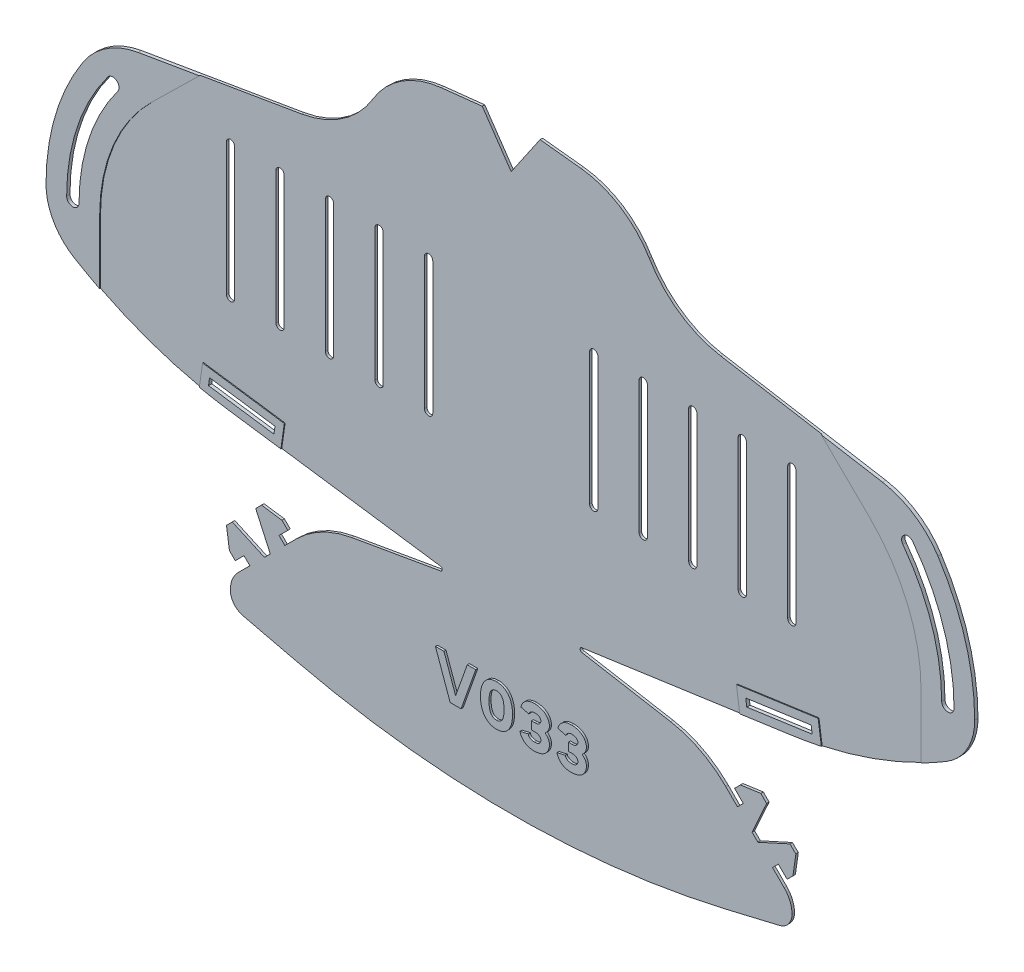
SolidWorks part; units mm, degrees
ref_plane "Front Plane" through (0, 0, 0) normal (0, 0, 1) x (1, 0, 0)
ref_plane "Top Plane" through (0, 0, 0) normal (0, 1, 0) x (1, 0, 0)
ref_plane "Right Plane" through (0, 0, 0) normal (1, 0, 0) x (0, 0, -1)
sketch "Sketch1" plane through (0, 0, 0) normal (0, 0, 1) x (1, 0, 0)
  line L0 (0, 0) -> (0, -145) construction
  line L1 (-14, -102) -> (14, -102) construction
  line L2 (-112.5, -69) -> (112.5, -69) construction
  line L3 (0, -10.2352) -> (-7, 0)
  line L4 (0, -10.2352) -> (7, 0)
  line L5 (7, 0) -> (16.9419, -1.0768)
  line L6 (-90.1804, -30.1909) -> (-50.7439, -23.5)
  line L7 (90.1804, -30.1909) -> (50.7439, -23.5)
  line L8 (-14, -102) -> (-68.2662, -94.2919)
  line L9 (-7, 0) -> (-16.9419, -1.0768)
  line L10 (14, -102) -> (68.2662, -94.2919)
  line L11 (-103.5977, -39) -> (-103.5977, -69) construction
  line L12 (-14, -102) -> (-38.6266, -106.305)
  line L13 (-52, -113.2546) -> (-54.8283, -116.0832)
  line L14 (52, -113.2546) -> (54.8283, -116.0832)
  line L15 (14, -102) -> (38.6266, -106.305)
  line L16 (-54.8283, -116.0832) -> (-56.2426, -114.669)
  line L17 (-56.2426, -114.669) -> (-54.1214, -112.5476)
  line L18 (-54.1214, -112.5476) -> (-55.5356, -111.1334)
  line L19 (-55.5356, -111.1334) -> (-60.4854, -110.4265)
  line L20 (-60.4854, -110.4265) -> (-68.9703, -118.9122)
  line L21 (-64.7275, -123.1546) -> (-63.3132, -124.5688)
  line L22 (-63.3132, -124.5688) -> (-66.1415, -127.3973)
  line L23 (-64.7275, -123.1546) -> (-66.8487, -125.2761)
  line L24 (-66.8487, -125.2761) -> (-68.263, -123.8619)
  line L25 (-68.9703, -118.9122) -> (-68.263, -123.8619)
  line L26 (68.9703, -118.9122) -> (68.263, -123.8619)
  line L27 (66.8487, -125.2761) -> (68.263, -123.8619)
  line L28 (64.7275, -123.1546) -> (66.8487, -125.2761)
  line L29 (63.3132, -124.5688) -> (66.1415, -127.3973)
  line L30 (64.7275, -123.1546) -> (63.3132, -124.5688)
  line L31 (60.4854, -110.4265) -> (68.9703, -118.9122)
  line L32 (55.5356, -111.1334) -> (60.4854, -110.4265)
  line L33 (54.1214, -112.5476) -> (55.5356, -111.1334)
  line L34 (56.2426, -114.669) -> (54.1214, -112.5476)
  line L35 (54.8283, -116.0832) -> (56.2426, -114.669)
  line L36 (-64.9691, -135.8852) -> (-52.4361, -138.8607)
  line L37 (64.9691, -135.8852) -> (52.4361, -138.8607)
  line L38 (-68.9703, -118.9122) -> (-64.7275, -123.1546) construction
  line L39 (-60.4854, -110.4265) -> (-56.2426, -114.669) construction
  arc A0 (-16.9419, -1.0768) -> (-33.4614, -11.6696) centre (-14.5729, -22.9489) ccw
  arc A1 (-33.4614, -11.6696) -> (-50.7439, -23.5) centre (-54.9257, 1.1478) cw
  arc A2 (-103.5977, -39) -> (-90.1804, -30.1909) centre (-86.8349, -49.9091) cw
  arc A3 (-112.5, -69) -> (-103.5977, -39) centre (-57.5, -69) cw
  arc A4 (112.5, -69) -> (103.5977, -39) centre (57.5, -69) ccw
  arc A5 (103.5977, -39) -> (90.1804, -30.1909) centre (86.8349, -49.9091) ccw
  arc A6 (16.9419, -1.0768) -> (33.4614, -11.6696) centre (14.5729, -22.9489) cw
  arc A7 (33.4614, -11.6696) -> (50.7439, -23.5) centre (54.9257, 1.1478) ccw
  arc A8 (-112.5, -69) -> (-105.7111, -81) centre (-98.5, -69) ccw
  arc A9 (-105.7111, -81) -> (-68.2662, -94.2919) centre (-54.2032, 4.7143) ccw
  arc A10 (112.5, -69) -> (105.7111, -81) centre (98.5, -69) cw
  arc A11 (105.7111, -81) -> (68.2662, -94.2919) centre (54.2032, 4.7143) cw
  arc A12 (-38.6266, -106.305) -> (-52, -113.2546) centre (-34.3216, -130.9315) ccw
  arc A13 (38.6266, -106.305) -> (52, -113.2546) centre (34.3216, -130.9315) cw
  arc A14 (-66.1415, -127.3973) -> (-68.0451, -131.9933) centre (-61.5451, -131.9933) ccw
  arc A15 (-68.0451, -131.9933) -> (-64.9691, -135.8852) centre (-64.0451, -131.9933) ccw
  arc A16 (68.0451, -131.9933) -> (64.9691, -135.8852) centre (64.0451, -131.9933) cw
  arc A17 (66.1415, -127.3973) -> (68.0451, -131.9933) centre (61.5451, -131.9933) cw
  arc A19 (-52.4361, -138.8607) -> (0, -145) centre (0, 82) ccw
  arc A20 (52.4361, -138.8607) -> (0, -145) centre (0, 82) cw
  point P8 (0, -102)
  point P11 (0, -69)
  dimension "D5" = 55
  dimension "D11" = 20
  dimension "D13" = 25
  dimension "D16" = 14
  dimension "D15" = 22
  dimension "D18" = 100
  dimension "D22" = 25
  dimension "D31" = 6.5
  dimension "D32" = 4
  dimension "D34" = 227
  dimension "D1" = 145
  dimension "D2" = 28
  dimension "D3" = 43
  dimension "D4" = 76
  dimension "D6" = 225
  dimension "D7" = 14
  dimension "D8" = 12.4
  dimension "D9" = 10
  dimension "D10" = 30
  dimension "D12" = 40
  dimension "D14" = 45.5
  dimension "D17" = 12
  dimension "D19" = 18
  dimension "D20" = 25
  dimension "D21" = 4
  dimension "D23" = 38
  dimension "D24" = 2
  dimension "D25" = 3
  dimension "D26" = 2
  dimension "D27" = 18
  dimension "D29" = 8
  dimension "D30" = 4
extrude "Main Shape" add sketch "Sketch1" along normal blind 0.6
sketch "Sketch2" plane through (0, 0, 0.6) normal (0, 0, 1) x (1, 0, 0)
  line L0 (0, -55) -> (0, 55) construction
  arc A0 (-96.3, -39.9) -> (-106, -69) centre (-57.5, -69) ccw construction
  arc A1 (-97.5, -39) -> (-107.5, -69) centre (-57.5, -69) ccw
  arc A2 (-95.1, -40.8) -> (-104.5, -69) centre (-57.5, -69) ccw
  arc A3 (-95.1, -40.8) -> (-97.5, -39) centre (-96.3, -39.9) ccw
  arc A4 (-107.5, -69) -> (-104.5, -69) centre (-106, -69) ccw
  arc A6 (-103.5977, -39) -> (-112.5, -69) centre (-57.5, -69) ccw construction
  arc A7 (96.3, -39.9) -> (106, -69) centre (57.5, -69) cw construction
  arc A8 (97.5, -39) -> (107.5, -69) centre (57.5, -69) cw
  arc A9 (95.1, -40.8) -> (104.5, -69) centre (57.5, -69) cw
  arc A10 (95.1, -40.8) -> (97.5, -39) centre (96.3, -39.9) cw
  arc A11 (107.5, -69) -> (104.5, -69) centre (106, -69) cw
  point P3 (-103.5111, -53.663)
  point P19 (103.5111, -53.663)
  dimension "D1" = 5
  dimension "D2" = 1.5
extrude "Elastic Attachment Points" cut sketch "Sketch2" against normal through all
sketch "Sketch7" plane through (0, 0, 0.6) normal (0, 0, 1) x (1, 0, 0)
  line L0 (-99.5, -69) -> (-99.5, -84.4384)
  line L1 (-86.8939, -39) -> (-75.3319, -27.6717)
  line L2 (-50.7439, -23.5) -> (-90.1804, -30.1909) construction
  line L3 (-75.3319, -27.6717) -> (-90.1804, -30.1909)
  line L4 (0, -55) -> (0, 55) construction
  line L5 (75.3319, -27.6717) -> (90.1804, -30.1909)
  line L6 (86.8939, -39) -> (75.3319, -27.6717)
  line L7 (99.5, -69) -> (99.5, -84.4384)
  arc A0 (-99.5, -69) -> (-86.8939, -39) centre (-57.5, -69) cw
  arc A1 (-95.1, -40.8) -> (-104.5, -69) centre (-57.5, -69) ccw construction
  arc A2 (-105.7111, -81) -> (-68.2662, -94.2919) centre (-54.2032, 4.7143) ccw construction
  arc A3 (-112.5, -69) -> (-105.7111, -81) centre (-98.5, -69) ccw construction
  arc A4 (-103.5977, -39) -> (-112.5, -69) centre (-57.5, -69) ccw construction
  arc A5 (-90.1804, -30.1909) -> (-103.5977, -39) centre (-86.8349, -49.9091) ccw construction
  arc A6 (-105.7111, -81) -> (-99.5, -84.4384) centre (-54.2032, 4.7143) ccw
  arc A7 (-112.5, -69) -> (-105.7111, -81) centre (-98.5, -69) ccw
  arc A8 (-103.5977, -39) -> (-112.5, -69) centre (-57.5, -69) ccw
  arc A9 (-90.1804, -30.1909) -> (-103.5977, -39) centre (-86.8349, -49.9091) ccw
  arc A10 (90.1804, -30.1909) -> (103.5977, -39) centre (86.8349, -49.9091) cw
  arc A11 (103.5977, -39) -> (112.5, -69) centre (57.5, -69) cw
  arc A12 (112.5, -69) -> (105.7111, -81) centre (98.5, -69) cw
  arc A13 (105.7111, -81) -> (99.5, -84.4384) centre (54.2032, 4.7143) cw
  arc A14 (99.5, -69) -> (86.8939, -39) centre (57.5, -69) ccw
  arc A15 (-107.5, -69) -> (-104.5, -69) centre (-106, -69) ccw construction
  arc A16 (-95.1, -40.8) -> (-97.5, -39) centre (-96.3, -39.9) ccw construction
  arc A17 (-97.5, -39) -> (-107.5, -69) centre (-57.5, -69) ccw construction
  arc A18 (-107.5, -69) -> (-104.5, -69) centre (-106, -69) ccw
  arc A19 (-95.1, -40.8) -> (-97.5, -39) centre (-96.3, -39.9) ccw
  arc A20 (-95.1, -40.8) -> (-104.5, -69) centre (-57.5, -69) ccw
  arc A21 (-97.5, -39) -> (-107.5, -69) centre (-57.5, -69) ccw
  arc A22 (104.5, -69) -> (107.5, -69) centre (106, -69) ccw construction
  arc A23 (97.5, -39) -> (95.1, -40.8) centre (96.3, -39.9) ccw construction
  arc A24 (104.5, -69) -> (95.1, -40.8) centre (57.5, -69) ccw construction
  arc A25 (107.5, -69) -> (97.5, -39) centre (57.5, -69) ccw construction
  arc A26 (104.5, -69) -> (107.5, -69) centre (106, -69) ccw
  arc A27 (97.5, -39) -> (95.1, -40.8) centre (96.3, -39.9) ccw
  arc A28 (104.5, -69) -> (95.1, -40.8) centre (57.5, -69) ccw
  arc A29 (107.5, -69) -> (97.5, -39) centre (57.5, -69) ccw
  dimension "D1" = 5
extrude "Reinforced Attachment Points" add sketch "Sketch7" along normal blind 0.2
sketch "Sketch6" plane through (0, 0, 0.6) normal (0, 0, 1) x (1, 0, 0)
  line L0 (-73.1225, -91.5821) -> (-57.2815, -93.8322)
  line L1 (-57.2815, -93.8322) -> (-57.0283, -92.05)
  line L2 (-57.0283, -92.05) -> (-72.8693, -89.8)
  line L3 (-72.8693, -89.8) -> (-73.1225, -91.5821)
  line L4 (-68.2662, -94.2919) -> (-14, -102) construction
  line L5 (-64.9488, -90.925) -> (-65.202, -92.7071) construction
  line L13 (0, -0.44) -> (0, 0.44) construction
  line L14 (64.9488, -90.925) -> (65.202, -92.7071) construction
  line L15 (73.1225, -91.5821) -> (72.8693, -89.8)
  line L16 (57.0283, -92.05) -> (57.2815, -93.8322)
  line L22 (57.0283, -92.05) -> (72.8693, -89.8)
  line L24 (73.1225, -91.5821) -> (57.2815, -93.8322)
  dimension "D1" = 2
  dimension "D2" = 16
  dimension "D3" = 52
  dimension "D4" = 1.8
extrude "Tab Slits" cut sketch "Sketch6" against normal through all
sketch "Sketch9" plane through (0, 0, 0.6) normal (0, 0, 1) x (1, 0, 0)
  line L4 (-57.2815, -93.8322) -> (-57.0283, -92.05) construction
  line L5 (-73.1225, -91.5821) -> (-57.2815, -93.8322) construction
  line L6 (-72.8693, -89.8) -> (-73.1225, -91.5821) construction
  line L7 (-57.0283, -92.05) -> (-72.8693, -89.8) construction
  line L12 (-57.2815, -93.8322) -> (-57.0283, -92.05)
  line L13 (-73.1225, -91.5821) -> (-57.2815, -93.8322)
  line L14 (-72.8693, -89.8) -> (-73.1225, -91.5821)
  line L15 (-57.0283, -92.05) -> (-72.8693, -89.8)
  line L16 (-55.5826, -96.0935) -> (-54.767, -90.3512)
  line L17 (-68.2662, -94.2919) -> (-14, -102) construction
  line L18 (-54.767, -90.3512) -> (-74.5682, -87.5386)
  line L19 (-74.5682, -87.5386) -> (-75.3475, -93.0248)
  line L20 (-68.2662, -94.2919) -> (-55.5826, -96.0935)
  line L21 (0, -0.44) -> (0, 0.44) construction
  line L22 (68.2662, -94.2919) -> (55.5826, -96.0935)
  line L23 (74.5682, -87.5386) -> (75.3475, -93.0248)
  line L24 (54.767, -90.3512) -> (74.5682, -87.5386)
  line L25 (55.5826, -96.0935) -> (54.767, -90.3512)
  line L26 (57.0283, -92.05) -> (72.8693, -89.8)
  line L27 (72.8693, -89.8) -> (73.1225, -91.5821)
  line L28 (73.1225, -91.5821) -> (57.2815, -93.8322)
  line L29 (57.2815, -93.8322) -> (57.0283, -92.05)
  arc A0 (-99.5, -84.4384) -> (-68.2662, -94.2919) centre (-54.2032, 4.7143) ccw construction
  arc A1 (-75.3475, -93.0248) -> (-68.2662, -94.2919) centre (-54.2032, 4.7143) ccw
  arc A2 (75.3475, -93.0248) -> (68.2662, -94.2919) centre (54.2032, 4.7143) cw
  dimension "D1" = 2
  dimension "D2" = 2
  dimension "D3" = 2
extrude "Reinforced Tab Slits" add sketch "Sketch9" along normal blind 0.2
sketch "Sketch11" plane through (0, 0, 0.6) normal (0, 0, 1) x (1, 0, 0)
  line L0 (-67.5562, -117.4979) -> (-59.7778, -121.0331)
  line L1 (-60.4854, -110.4265) -> (-68.9703, -118.9122) construction
  line L2 (-59.7778, -121.0331) -> (-58.3637, -119.6188)
  line L3 (-58.3637, -119.6188) -> (-61.8996, -111.8408)
  line L4 (-61.8996, -111.8408) -> (-67.5562, -117.4979)
  line L6 (-58.3637, -119.6188) -> (-54.8283, -116.0832) construction
  line L7 (-59.7778, -121.0331) -> (-63.3132, -124.5688) construction
  line L10 (0, -0.44) -> (0, 0.44) construction
  line L11 (59.7778, -121.0331) -> (63.3132, -124.5688) construction
  line L12 (58.3637, -119.6188) -> (54.8283, -116.0832) construction
  line L13 (61.8996, -111.8408) -> (67.5562, -117.4979)
  line L14 (58.3637, -119.6188) -> (61.8996, -111.8408)
  line L15 (59.7778, -121.0331) -> (58.3637, -119.6188)
  line L16 (67.5562, -117.4979) -> (59.7778, -121.0331)
  dimension "D1" = 2
  dimension "D2" = 2
  dimension "D3" = 5
extrude "Tab Flex Relief" cut sketch "Sketch11" against normal through all both and the other way through all
sketch "Sketch3" plane through (0, 0, 0.6) normal (0, 0, 1) x (1, 0, 0)
  line L0 (-20, -38.45) -> (-20, -70.45) construction
  line L1 (-19, -38.45) -> (-19, -70.45)
  line L2 (-21, -38.45) -> (-21, -70.45)
  line L3 (0, -10.2352) -> (0, -145) construction
  line L4 (-106, -69) -> (-96.3, -69) construction
  line L5 (-96.3, -69) -> (-96.3, -39.9) construction
  line L6 (-32, -38.45) -> (-32, -70.45) construction
  line L7 (-31, -38.45) -> (-31, -70.45)
  line L8 (-33, -38.45) -> (-33, -70.45)
  line L9 (-44, -38.45) -> (-44, -70.45) construction
  line L10 (-43, -38.45) -> (-43, -70.45)
  line L11 (-45, -38.45) -> (-45, -70.45)
  line L12 (-56, -38.45) -> (-56, -70.45) construction
  line L13 (-55, -38.45) -> (-55, -70.45)
  line L14 (-57, -38.45) -> (-57, -70.45)
  line L15 (-68, -38.45) -> (-68, -70.45) construction
  line L16 (-67, -38.45) -> (-67, -70.45)
  line L17 (-69, -38.45) -> (-69, -70.45)
  line L18 (20, -38.45) -> (20, -70.45) construction
  line L19 (19, -38.45) -> (19, -70.45)
  line L20 (21, -38.45) -> (21, -70.45)
  line L21 (32, -38.45) -> (32, -70.45) construction
  line L22 (31, -38.45) -> (31, -70.45)
  line L23 (33, -38.45) -> (33, -70.45)
  line L24 (44, -38.45) -> (44, -70.45) construction
  line L25 (43, -38.45) -> (43, -70.45)
  line L26 (45, -38.45) -> (45, -70.45)
  line L27 (56, -38.45) -> (56, -70.45) construction
  line L28 (55, -38.45) -> (55, -70.45)
  line L29 (57, -38.45) -> (57, -70.45)
  line L30 (68, -38.45) -> (68, -70.45) construction
  line L31 (67, -38.45) -> (67, -70.45)
  line L32 (69, -38.45) -> (69, -70.45)
  arc A0 (-19, -38.45) -> (-21, -38.45) centre (-20, -38.45) ccw
  arc A1 (-21, -70.45) -> (-19, -70.45) centre (-20, -70.45) ccw
  arc A2 (-52.4361, -138.8607) -> (52.4361, -138.8607) centre (0, 82) ccw construction
  arc A3 (-31, -38.45) -> (-33, -38.45) centre (-32, -38.45) ccw
  arc A4 (-33, -70.45) -> (-31, -70.45) centre (-32, -70.45) ccw
  arc A5 (-43, -38.45) -> (-45, -38.45) centre (-44, -38.45) ccw
  arc A6 (-45, -70.45) -> (-43, -70.45) centre (-44, -70.45) ccw
  arc A7 (-55, -38.45) -> (-57, -38.45) centre (-56, -38.45) ccw
  arc A8 (-57, -70.45) -> (-55, -70.45) centre (-56, -70.45) ccw
  arc A9 (-67, -38.45) -> (-69, -38.45) centre (-68, -38.45) ccw
  arc A10 (-69, -70.45) -> (-67, -70.45) centre (-68, -70.45) ccw
  arc A11 (19, -38.45) -> (21, -38.45) centre (20, -38.45) cw
  arc A12 (21, -70.45) -> (19, -70.45) centre (20, -70.45) cw
  arc A13 (31, -38.45) -> (33, -38.45) centre (32, -38.45) cw
  arc A14 (33, -70.45) -> (31, -70.45) centre (32, -70.45) cw
  arc A15 (43, -38.45) -> (45, -38.45) centre (44, -38.45) cw
  arc A16 (45, -70.45) -> (43, -70.45) centre (44, -70.45) cw
  arc A17 (55, -38.45) -> (57, -38.45) centre (56, -38.45) cw
  arc A18 (57, -70.45) -> (55, -70.45) centre (56, -70.45) cw
  arc A19 (67, -38.45) -> (69, -38.45) centre (68, -38.45) cw
  arc A20 (69, -70.45) -> (67, -70.45) centre (68, -70.45) cw
  point P2 (-20, -54.45)
  point P13 (-19, -54.45)
  point P16 (-96.3, -54.45)
  point P20 (-32, -54.45)
  point P31 (-44, -54.45)
  point P38 (-56, -54.45)
  point P45 (-68, -54.45)
  point P52 (20, -54.45)
  point P59 (32, -54.45)
  point P66 (44, -54.45)
  point P73 (56, -54.45)
  point P80 (68, -54.45)
  dimension "D1" = 2
  dimension "D2" = 32
  dimension "D3" = 20
  dimension "D4" = 5
  dimension "D5" = 10
extrude "Breathing Slits" cut sketch "Sketch3" against normal through all
sketch "Sketch8" plane through (0, 0, 0.6) normal (0, 0, 1) x (1, 0, 0)
  line L0 (-67.0266, -128.5) -> (67.0266, -128.5) construction
  line L1 (0, -10.2352) -> (0, -145) construction
  arc A0 (-52.4361, -138.8607) -> (52.4361, -138.8607) centre (0, 82) ccw construction
  arc A1 (-66.1415, -127.3973) -> (-68.0451, -131.9933) centre (-61.5451, -131.9933) ccw construction
  text T0 "<b>V033</b>" font "Double Porter 3" height 10
  point P9 (0, -128.5)
  dimension "D2" = 16.5
extrude "Version Number" add sketch "Sketch8" along normal blind 0.5
fillet "Fillet1" radius 0.5 2 edges at (-14, -102, 0.3) (14, -102, 0.3)
